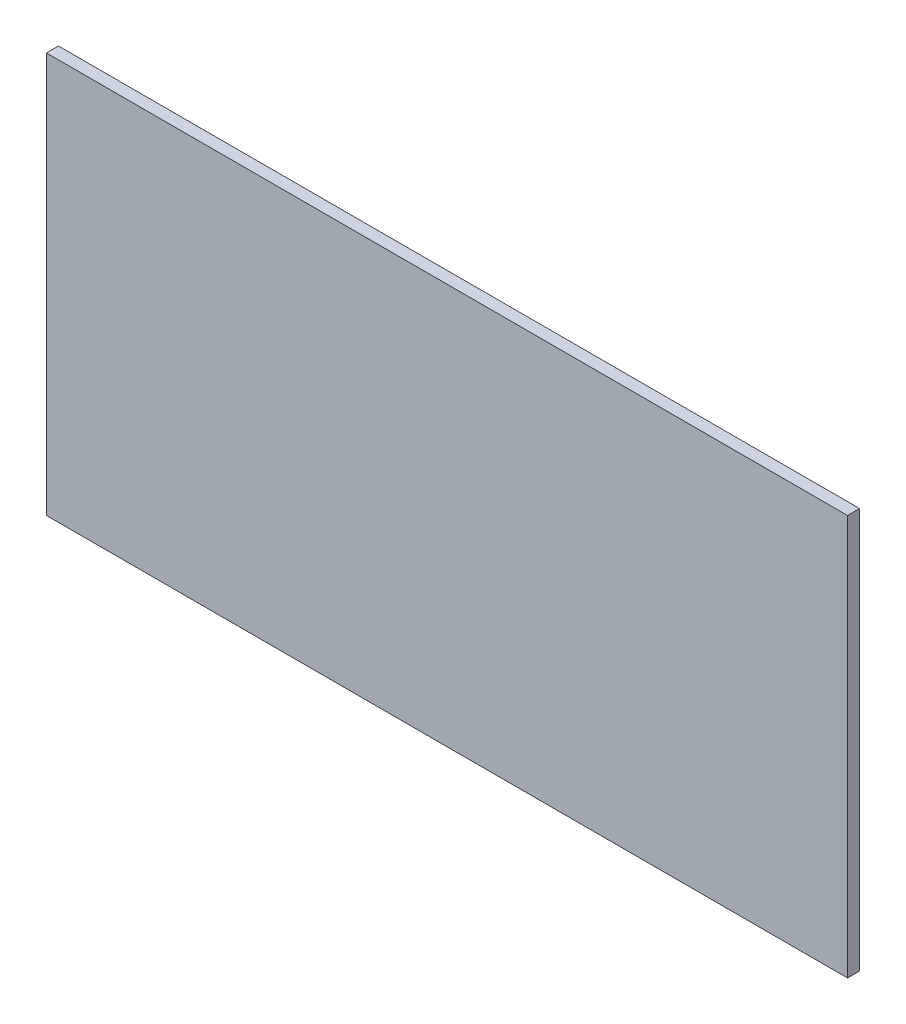
SolidWorks part; units mm, degrees
ref_plane "Plan de face" through (0, 0, 0) normal (0, 0, 1) x (1, 0, 0)
ref_plane "Plan de dessus" through (0, 0, 0) normal (0, 1, 0) x (1, 0, 0)
ref_plane "Plan de droite" through (0, 0, 0) normal (1, 0, 0) x (0, 0, -1)
sketch "Sketch1" plane through (0, 0, 0) normal (0, 0, 1) x (1, 0, 0)
  line L1 (-100, -50) -> (100, -50)
  line L2 (-100, -50) -> (-100, 50)
  line L3 (-100, 50) -> (100, 50)
  line L4 (100, -50) -> (100, 50)
  line L5 (-100, -50) -> (100, 50) construction
  line L6 (-100, 50) -> (100, -50) construction
  point P0 (0, 0)
  dimension "D1" = 200
  dimension "D2" = 100
extrude "Boss-Extrude1" add sketch "Sketch1" along normal blind 3
